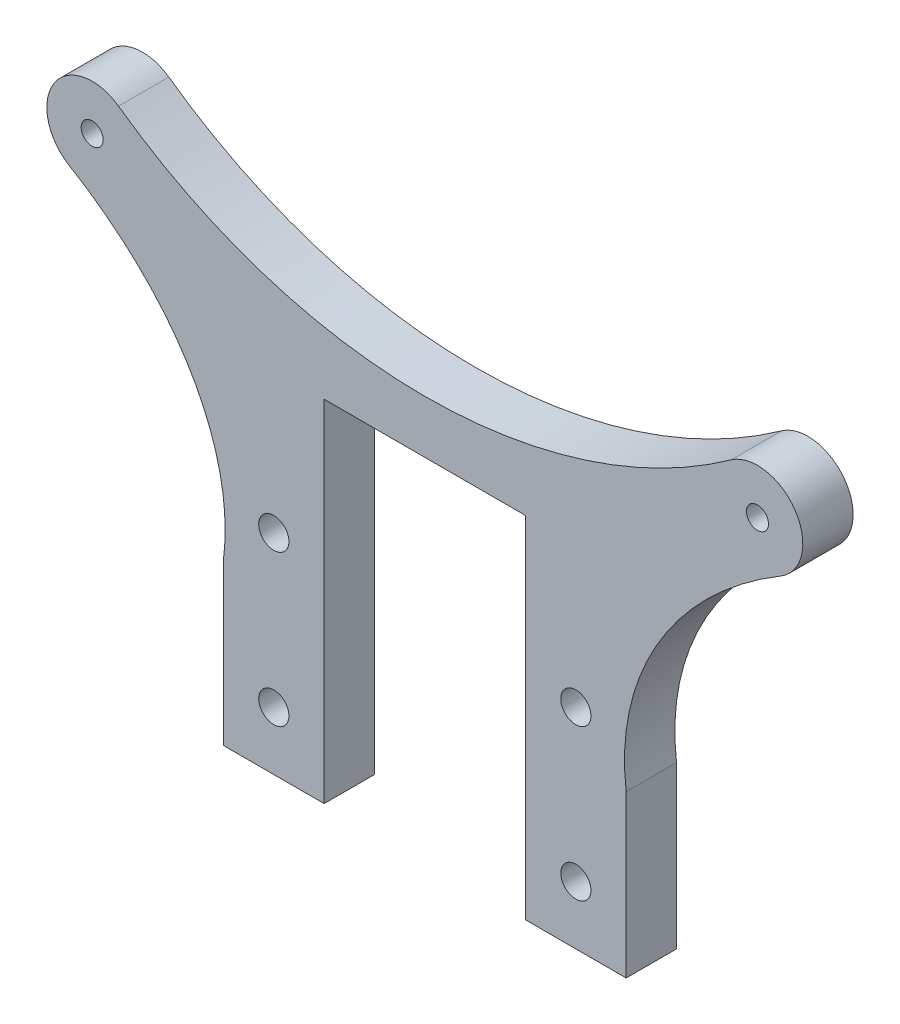
SolidWorks part; units mm, degrees
ref_plane "Front Plane" through (0, 0, 0) normal (0, 0, 1) x (1, 0, 0)
ref_plane "Top Plane" through (0, 0, 0) normal (0, 1, 0) x (1, 0, 0)
ref_plane "Right Plane" through (0, 0, 0) normal (1, 0, 0) x (0, 0, -1)
sketch "Sketch1" plane through (0, 0, 0) normal (0, 0, 1) x (1, 0, 0)
  line L0 (0, 32.7025) -> (0, -57.25) construction
  line L1 (-12.7, 0) -> (12.7, 0)
  line L2 (-12.7, 0) -> (-12.7, -44.1799)
  line L3 (-25.4, -44.1799) -> (-12.7, -44.1799)
  line L4 (-25.4, -23.823) -> (-25.4, -44.1799)
  line L5 (25.4, -23.823) -> (25.4, -44.1799)
  line L6 (25.4, -44.1799) -> (12.7, -44.1799)
  line L7 (12.7, 0) -> (12.7, -44.1799)
  circle A0 centre (41.9643, 14.3938) radius 1.3891
  arc A1 (-38.6411, 19.0466) -> (-44.9019, 9.4883) centre (-41.9643, 14.3938) ccw
  arc A2 (38.6411, 19.0466) -> (-38.6411, 19.0466) centre (0, 73.1494) cw
  arc A3 (38.6411, 19.0466) -> (44.9019, 9.4883) centre (41.9643, 14.3938) cw
  circle A4 centre (-41.9643, 14.3938) radius 1.3891
  circle A5 centre (-19.05, -17.78) radius 1.905
  circle A6 centre (-19.05, -36.83) radius 1.905
  circle A7 centre (19.05, -36.83) radius 1.905
  circle A8 centre (19.05, -17.78) radius 1.905
  ellipse E0 centre (-73.0063, -17.7906) end of major axis (-25.4, -23.823) minor radius 35.5582 (-44.9019, 9.4883) -> (-25.4, -23.823) cw
  ellipse E1 centre (73.0063, -17.7906) end of major axis (25.4, -23.823) minor radius 35.5582 (44.9019, 9.4883) -> (25.4, -23.823) ccw
  point P9 (-41.9643, 14.3938)
  point P14 (0, 6.6644)
  point P28 (0, 0)
  point P34 (0, 0)
  dimension "D4" = 19.05
  dimension "D5" = 3.81
  dimension "D1" = 12.7
  dimension "D2" = 25.4
  dimension "D3" = 17.78
  dimension "D6" = 41.9643
extrude "Boss-Extrude1" add sketch "Sketch1" along normal blind 6.35
